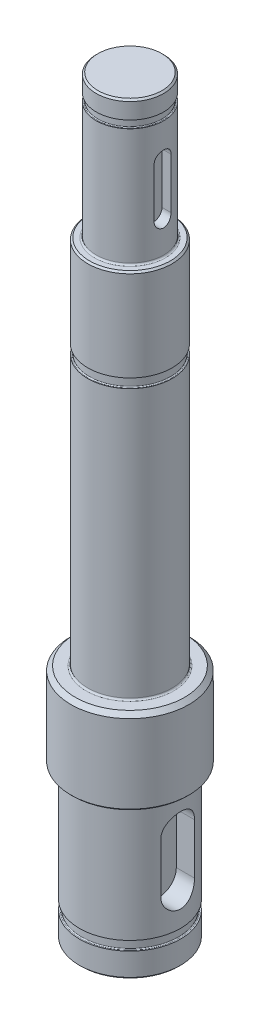
SolidWorks part; units mm, degrees
ref_plane "Front" through (0, 0, 0) normal (0, 0, 1) x (1, 0, 0)
ref_plane "Top" through (0, 0, 0) normal (0, 1, 0) x (1, 0, 0)
ref_plane "Right" through (0, 0, 0) normal (1, 0, 0) x (0, 0, -1)
sketch "Sketch1" plane through (0, 0, 0) normal (1, 0, 0) x (0, 0, -1)
  line L0 (0, 27.8978) -> (0, -35.2793) construction
  line L1 (0, 0) -> (0, -89)
  line L2 (0, -89) -> (6, -89)
  line L3 (6, -89) -> (6, -71)
  line L4 (6, -71) -> (7, -71)
  line L5 (7, -71) -> (7, -61)
  line L6 (7, -61) -> (5, -61)
  line L7 (4, -17) -> (4, 0)
  line L8 (4, 0) -> (0, 0)
  line L10 (5, -17) -> (5, -61)
  line L11 (4, -17) -> (5, -17)
  dimension "D2" = 4
  dimension "D3" = 2
  dimension "D4" = 10
  dimension "D5" = 18
  dimension "D6" = 44
  dimension "D7" = 1
  dimension "D9" = 17
  dimension "D10" = 6
revolve "Revolve1" add sketch "Sketch1" angle 360 about L0
ref_plane "Plane1" through (0, 27.8978, 0) normal (-1, 0, 0) x (0, 0, 1)
sketch "Sketch3" plane through (0, 27.8978, 0) normal (-1, 0, 0) x (0, 0, 1)
  line L0 (4.91, -91.8478) -> (6, -91.8478)
  line L1 (6, -91.8478) -> (6, -104.8978)
  line L2 (6, -104.8978) -> (4.91, -104.8978)
  line L3 (4.8, -105.0078) -> (4.8, -91.7378)
  line L4 (0, -50) -> (0, 50) construction
  line L5 (-7, -98.8978) -> (7, -98.8978) construction
  arc A0 (4.8, -91.7378) -> (4.91, -91.8478) centre (4.91, -91.7378) ccw
  arc A1 (4.8, -105.0078) -> (4.91, -104.8978) centre (4.91, -105.0078) cw
  dimension "D1" = 0.11
  dimension "D2" = 0.11
  dimension "D3" = 6
revolve "Groove for BS 3673 P4 - S010M, External Circlip1" cut sketch "Sketch3"
ref_plane "Plane2" through (0, 27.8978, 0) normal (-1, 0, 0) x (0, 0, 1)
ref_plane "Plane3" through (0, 27.8978, 0) normal (-1, 0, 0) x (0, 0, 1)
sketch "Sketch7" plane through (0, 27.8978, 0) normal (-1, 0, 0) x (0, 0, 1)
  line L0 (5.86, -74.8978) -> (9.0688, -74.8978)
  line L1 (9.0688, -74.8978) -> (8.463, -73.9796)
  line L2 (8.463, -73.9796) -> (5.9673, -62.8836)
  line L3 (5.75, -62.9078) -> (5.75, -74.7878)
  line L4 (0, -50) -> (0, 50) construction
  line L5 (7, -88.8978) -> (-7, -88.8978) construction
  arc A0 (5.75, -74.7878) -> (5.86, -74.8978) centre (5.86, -74.7878) ccw
  arc A1 (5.75, -62.9078) -> (5.9673, -62.8836) centre (5.86, -62.9078) cw
  dimension "D1" = 0.11
  dimension "D2" = 0.11
  dimension "D3" = 1.1
  dimension "D4" = 14
revolve "Groove for BS 3673 P4 - S012M, External Circlip1" cut sketch "Sketch7" angle 360 about L4
ref_plane "Plane4" through (0, 27.8978, 0) normal (-1, 0, 0) x (0, 0, 1)
ref_plane "Plane5" through (0, 27.8978, 0) normal (-1, 0, 0) x (0, 0, 1)
sketch "Sketch9" plane through (0, 27.8978, 0) normal (-1, 0, 0) x (0, 0, 1)
  line L0 (5.86, -113.9978) -> (7.2, -113.9978)
  line L1 (7.2, -113.9978) -> (7.2, -112.8978)
  line L2 (7.2, -112.8978) -> (5.86, -112.8978)
  line L3 (5.75, -113.0078) -> (5.75, -113.8878)
  line L4 (0, -50) -> (0, 50) construction
  line L5 (-7, -98.8978) -> (7, -98.8978) construction
  arc A0 (5.75, -113.8878) -> (5.86, -113.9978) centre (5.86, -113.8878) ccw
  arc A1 (5.75, -113.0078) -> (5.86, -112.8978) centre (5.86, -113.0078) cw
  dimension "D1" = 0.11
  dimension "D2" = 0.11
  dimension "D3" = 1.1
  dimension "D4" = 1.34
  dimension "D5" = 14
  dimension "D6" = 5.75
revolve "Groove for BS 3673 P4 - S012M, External Circlip2" cut sketch "Sketch9" angle 360 about L4
ref_plane "Plane6" through (0, 27.8978, 0) normal (-1, 0, 0) x (0, 0, 1)
sketch "Sketch11" plane through (0, 27.8978, 0) normal (-1, 0, 0) x (0, 0, 1)
  line L0 (4.91, -56.8978) -> (6, -56.8978)
  line L1 (6, -56.8978) -> (6, -55.7978)
  line L2 (6, -55.7978) -> (4.91, -55.7978)
  line L3 (4.8, -55.9078) -> (4.8, -56.7878)
  line L4 (0, -50) -> (0, 50) construction
  line L5 (7, -88.8978) -> (-7, -88.8978) construction
  arc A0 (4.8, -56.7878) -> (4.91, -56.8978) centre (4.91, -56.7878) ccw
  arc A1 (4.8, -55.9078) -> (4.91, -55.7978) centre (4.91, -55.9078) cw
  dimension "D1" = 0.11
  dimension "D2" = 0.11
  dimension "D3" = 4.8
  dimension "D4" = 6
  dimension "D5" = 1.1
  dimension "D6" = 32
revolve "Groove for BS 3673 P4 - S010M, External Circlip2" cut sketch "Sketch11" angle 360 about L4
ref_plane "Plane7" through (0, 27.8978, 0) normal (-1, 0, 0) x (0, 0, 1)
sketch "Sketch13" plane through (0, 27.8978, 0) normal (-1, 0, 0) x (0, 0, 1)
  line L0 (3.89, -30.8978) -> (4.8, -30.8978)
  line L1 (4.8, -30.8978) -> (4.8, -29.9978)
  line L2 (4.8, -29.9978) -> (3.89, -29.9978)
  line L3 (3.8, -30.0878) -> (3.8, -30.8078)
  line L4 (0, -50) -> (0, 50) construction
  line L5 (5, -44.8978) -> (-5, -44.8978) construction
  arc A0 (3.8, -30.8078) -> (3.89, -30.8978) centre (3.89, -30.8078) ccw
  arc A1 (3.8, -30.0878) -> (3.89, -29.9978) centre (3.89, -30.0878) cw
  dimension "D1" = 0.09
  dimension "D2" = 0.09
  dimension "D3" = 3.8
  dimension "D4" = 0.91
  dimension "D5" = 0.9
  dimension "D6" = 14
revolve "Groove for BS 3673 P4 - S008M, External Circlip1" cut sketch "Sketch13" angle 360 about L4
chamfer "Chamfer1" distance 0.5 angle 45 1 edges at (0, -61, 7)
chamfer "Chamfer2" distance 0.2 angle 45 4 edges at (0, 0, 4) (0, -17, 5) (0, -89, 6) (0, -71, 7)
fillet "Fillet1" radius 0.2 3 edges at (0, -17, 4) (0, -71, 6) (0, -61, 5)
ref_plane "Plane8" through (3.5, 0, 0) normal (1, 0, 0) x (0, 0, -1)
sketch "Sketch14" plane through (3.5, 0, 0) normal (1, 0, 0) x (0, 0, -1)
  line L0 (0, -81) -> (0, -75) construction
  line L1 (-2, -81) -> (-2, -75)
  line L2 (2, -81) -> (2, -75)
  line L3 (-6.8, -71) -> (6.8, -71) construction
  arc A0 (-2, -81) -> (2, -81) centre (0, -81) ccw
  arc A1 (2, -75) -> (-2, -75) centre (0, -75) ccw
  point P3 (0, -78)
  dimension "D1" = 2
  dimension "D2" = 7
  dimension "D3" = 6
extrude "Cut-Extrude1" cut sketch "Sketch14" along normal through all
ref_plane "Plane9" through (2.8, 0, 0) normal (1, 0, 0) x (0, 0, -1)
sketch "Sketch15" plane through (2.8, 0, 0) normal (1, 0, 0) x (0, 0, -1)
  line L0 (0, -13) -> (0, -7) construction
  line L1 (-1, -13) -> (-1, -7)
  line L2 (1, -13) -> (1, -7)
  line L3 (4.8, -17) -> (-4.8, -17) construction
  arc A0 (-1, -13) -> (1, -13) centre (0, -13) ccw
  arc A1 (1, -7) -> (-1, -7) centre (0, -7) ccw
  point P3 (0, -10)
  dimension "D2" = 1
  dimension "D1" = 7
  dimension "D3" = 6
extrude "Cut-Extrude2" cut sketch "Sketch15" along normal through all
